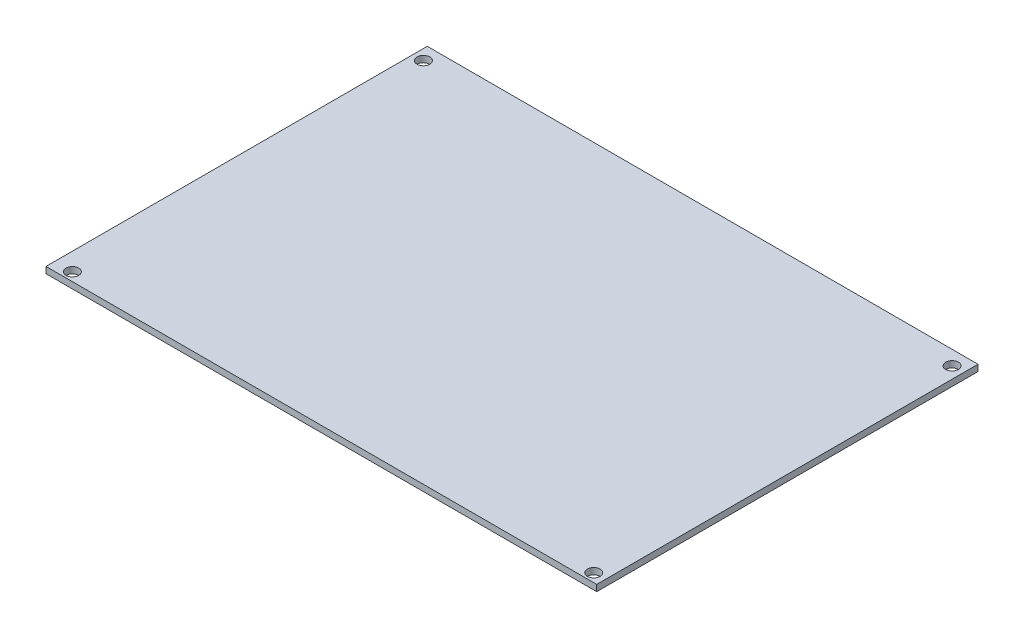
SolidWorks part; units mm, degrees
ref_plane "Front Plane" through (0, 0, 0) normal (0, 0, 1) x (1, 0, 0)
ref_plane "Top Plane" through (0, 0, 0) normal (0, 1, 0) x (1, 0, 0)
ref_plane "Right Plane" through (0, 0, 0) normal (1, 0, 0) x (0, 0, -1)
sketch "Sketch1" plane through (0, 0, 0) normal (0, 1, 0) x (1, 0, 0)
  line L1 (-65, 45) -> (65, 45)
  line L2 (-65, 45) -> (-65, -45)
  line L3 (-65, -45) -> (65, -45)
  line L4 (65, 45) -> (65, -45)
  line L5 (-65, 45) -> (65, -45) construction
  line L6 (-65, -45) -> (65, 45) construction
  point P0 (0, 0)
extrude "Boss-Extrude1" add sketch "Sketch1" along normal blind 1.5
sketch "Sketch2" plane through (0, 1.5, 0) normal (0, 1, 0) x (1, 0, 0)
  circle A0 centre (-62.5298, 41.6189) radius 1.5
  circle A1 centre (62.2591, 41.6189) radius 1.5
  circle A2 centre (62.2591, -42.9723) radius 1.5
  circle A3 centre (-60.7965, -42.9723) radius 1.5
extrude "Cut-Extrude1" cut sketch "Sketch2" against normal through all
